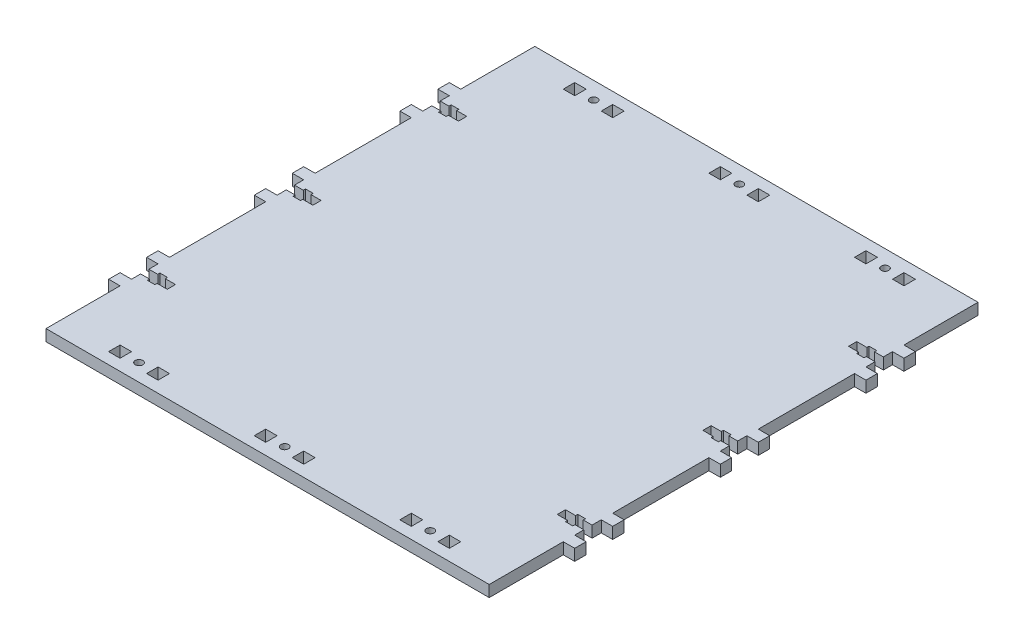
SolidWorks part; units mm, degrees
ref_plane "Front Plane" through (0, 0, 0) normal (0, 0, 1) x (1, 0, 0)
ref_plane "Top Plane" through (0, 0, 0) normal (0, 1, 0) x (1, 0, 0)
ref_plane "Right Plane" through (0, 0, 0) normal (1, 0, 0) x (0, 0, -1)
sketch "Sketch1" plane through (0, 0, 0) normal (0, 1, 0) x (1, 0, 0)
  line L0 (0, 0) -> (0, 159.925) construction
  line L1 (-175, -175) -> (175, -175) construction
  line L2 (-175, -175) -> (-175, 175) construction
  line L3 (-175, 175) -> (175, 175) construction
  line L4 (175, -175) -> (175, 175) construction
  line L5 (-175, -175) -> (175, 175) construction
  line L6 (-175, 175) -> (175, -175) construction
  line L7 (-175, -193) -> (175, -193)
  line L8 (-175, -193) -> (-175, 193)
  line L9 (-175, 193) -> (175, 193)
  line L10 (175, -193) -> (175, 193)
  line L11 (-175, -193) -> (175, 193) construction
  line L12 (-175, 193) -> (175, -193) construction
  line L13 (0, 0) -> (-128.731, 0) construction
  point P0 (0, 0)
  point P6 (0, 0)
  line B0 (0, 179.525) -> (-15, 179.525) construction
  line B1 (0, 184.9951) -> (0, 174.5131) construction
  line B2 (19.525, 184.05) -> (10.475, 184.05)
  line B3 (-19.525, 175) -> (-10.475, 175)
  line B4 (-19.525, 175) -> (-19.525, 184.05)
  line B5 (-19.525, 184.05) -> (-10.475, 184.05)
  line B6 (-10.475, 175) -> (-10.475, 184.05)
  line B7 (-19.525, 175) -> (-10.475, 184.05) construction
  line B8 (-19.525, 184.05) -> (-10.475, 175) construction
  line B9 (10.475, 175) -> (10.475, 184.05)
  line B10 (19.525, 175) -> (10.475, 175)
  line B11 (19.525, 175) -> (19.525, 184.05)
  circle B12 centre (0, 179.525) radius 3
  line B13 (-115, 179.525) -> (-130, 179.525) construction
  line B14 (-115, 184.9951) -> (-115, 174.5131) construction
  line B15 (-95.475, 184.05) -> (-104.525, 184.05)
  line B16 (-134.525, 175) -> (-125.475, 175)
  line B17 (-134.525, 175) -> (-134.525, 184.05)
  line B18 (-134.525, 184.05) -> (-125.475, 184.05)
  line B19 (-125.475, 175) -> (-125.475, 184.05)
  line B20 (-134.525, 175) -> (-125.475, 184.05) construction
  line B21 (-134.525, 184.05) -> (-125.475, 175) construction
  line B22 (-104.525, 175) -> (-104.525, 184.05)
  line B23 (-95.475, 175) -> (-104.525, 175)
  line B24 (-95.475, 175) -> (-95.475, 184.05)
  circle B25 centre (-115, 179.525) radius 3
  line B26 (-175, 19.5) -> (-184, 19.5)
  line B27 (-184, 19.5) -> (-184, 10.5)
  line B28 (-184, 10.5) -> (-175, 10.5)
  line B29 (-175, 10.5) -> (-175, 3.25)
  line B30 (-175, 3.25) -> (-168, 3.25)
  line B31 (-168, 3.25) -> (-168, 4.975)
  line B32 (-168, 4.975) -> (-162, 4.975)
  line B33 (-162, 4.975) -> (-162, 3.25)
  line B34 (-162, 3.25) -> (-154, 3.25)
  line B35 (-154, 3.25) -> (-154, -3.25)
  line B36 (-154, 0) -> (-175, 0) construction
  line B37 (-162, -3.25) -> (-154, -3.25)
  line B38 (-162, -4.975) -> (-162, -3.25)
  line B39 (-168, -4.975) -> (-162, -4.975)
  line B40 (-168, -3.25) -> (-168, -4.975)
  line B41 (-175, -3.25) -> (-168, -3.25)
  line B42 (-175, -10.5) -> (-175, -3.25)
  line B43 (-184, -10.5) -> (-175, -10.5)
  line B44 (-184, -19.5) -> (-184, -10.5)
  line B45 (-175, -19.5) -> (-184, -19.5)
  line B46 (-175, 134.5) -> (-184, 134.5)
  line B47 (-184, 134.5) -> (-184, 125.5)
  line B48 (-184, 125.5) -> (-175, 125.5)
  line B49 (-175, 125.5) -> (-175, 118.25)
  line B50 (-175, 118.25) -> (-168, 118.25)
  line B51 (-168, 118.25) -> (-168, 119.975)
  line B52 (-168, 119.975) -> (-162, 119.975)
  line B53 (-162, 119.975) -> (-162, 118.25)
  line B54 (-162, 118.25) -> (-154, 118.25)
  line B55 (-154, 118.25) -> (-154, 111.75)
  line B56 (-154, 115) -> (-175, 115) construction
  line B57 (-162, 111.75) -> (-154, 111.75)
  line B58 (-162, 110.025) -> (-162, 111.75)
  line B59 (-168, 110.025) -> (-162, 110.025)
  line B60 (-168, 111.75) -> (-168, 110.025)
  line B61 (-175, 111.75) -> (-168, 111.75)
  line B62 (-175, 104.5) -> (-175, 111.75)
  line B63 (-184, 104.5) -> (-175, 104.5)
  line B64 (-184, 95.5) -> (-184, 104.5)
  line B65 (-175, 95.5) -> (-184, 95.5)
  line B66 (115, 179.525) -> (130, 179.525) construction
  line B67 (115, 184.9951) -> (115, 174.5131) construction
  line B68 (95.475, 184.05) -> (104.525, 184.05)
  line B69 (134.525, 175) -> (125.475, 175)
  line B70 (134.525, 175) -> (134.525, 184.05)
  line B71 (134.525, 184.05) -> (125.475, 184.05)
  line B72 (125.475, 175) -> (125.475, 184.05)
  line B73 (134.525, 175) -> (125.475, 184.05) construction
  line B74 (134.525, 184.05) -> (125.475, 175) construction
  line B75 (104.525, 175) -> (104.525, 184.05)
  line B76 (95.475, 175) -> (104.525, 175)
  line B77 (95.475, 175) -> (95.475, 184.05)
  circle B78 centre (115, 179.525) radius 3
  line B79 (175, 19.5) -> (184, 19.5)
  line B80 (184, 19.5) -> (184, 10.5)
  line B81 (184, 10.5) -> (175, 10.5)
  line B82 (175, 10.5) -> (175, 3.25)
  line B83 (175, 3.25) -> (168, 3.25)
  line B84 (168, 3.25) -> (168, 4.975)
  line B85 (168, 4.975) -> (162, 4.975)
  line B86 (162, 4.975) -> (162, 3.25)
  line B87 (162, 3.25) -> (154, 3.25)
  line B88 (154, 3.25) -> (154, -3.25)
  line B89 (154, 0) -> (175, 0) construction
  line B90 (162, -3.25) -> (154, -3.25)
  line B91 (162, -4.975) -> (162, -3.25)
  line B92 (168, -4.975) -> (162, -4.975)
  line B93 (168, -3.25) -> (168, -4.975)
  line B94 (175, -3.25) -> (168, -3.25)
  line B95 (175, -10.5) -> (175, -3.25)
  line B96 (184, -10.5) -> (175, -10.5)
  line B97 (184, -19.5) -> (184, -10.5)
  line B98 (175, -19.5) -> (184, -19.5)
  line B99 (175, 134.5) -> (184, 134.5)
  line B100 (184, 134.5) -> (184, 125.5)
  line B101 (184, 125.5) -> (175, 125.5)
  line B102 (175, 125.5) -> (175, 118.25)
  line B103 (175, 118.25) -> (168, 118.25)
  line B104 (168, 118.25) -> (168, 119.975)
  line B105 (168, 119.975) -> (162, 119.975)
  line B106 (162, 119.975) -> (162, 118.25)
  line B107 (162, 118.25) -> (154, 118.25)
  line B108 (154, 118.25) -> (154, 111.75)
  line B109 (154, 115) -> (175, 115) construction
  line B110 (162, 111.75) -> (154, 111.75)
  line B111 (162, 110.025) -> (162, 111.75)
  line B112 (168, 110.025) -> (162, 110.025)
  line B113 (168, 111.75) -> (168, 110.025)
  line B114 (175, 111.75) -> (168, 111.75)
  line B115 (175, 104.5) -> (175, 111.75)
  line B116 (184, 104.5) -> (175, 104.5)
  line B117 (184, 95.5) -> (184, 104.5)
  line B118 (175, 95.5) -> (184, 95.5)
  line B119 (-115, -179.525) -> (-130, -179.525) construction
  line B120 (-115, -184.9951) -> (-115, -174.5131) construction
  line B121 (-95.475, -184.05) -> (-104.525, -184.05)
  line B122 (-134.525, -175) -> (-125.475, -175)
  line B123 (-134.525, -175) -> (-134.525, -184.05)
  line B124 (-134.525, -184.05) -> (-125.475, -184.05)
  line B125 (-125.475, -175) -> (-125.475, -184.05)
  line B126 (-134.525, -175) -> (-125.475, -184.05) construction
  line B127 (-134.525, -184.05) -> (-125.475, -175) construction
  line B128 (-104.525, -175) -> (-104.525, -184.05)
  line B129 (-95.475, -175) -> (-104.525, -175)
  line B130 (-95.475, -175) -> (-95.475, -184.05)
  circle B131 centre (-115, -179.525) radius 3
  line B132 (0, -179.525) -> (-15, -179.525) construction
  line B133 (0, -184.9951) -> (0, -174.5131) construction
  line B134 (19.525, -184.05) -> (10.475, -184.05)
  line B135 (-19.525, -175) -> (-10.475, -175)
  line B136 (-19.525, -175) -> (-19.525, -184.05)
  line B137 (-19.525, -184.05) -> (-10.475, -184.05)
  line B138 (-10.475, -175) -> (-10.475, -184.05)
  line B139 (-19.525, -175) -> (-10.475, -184.05) construction
  line B140 (-19.525, -184.05) -> (-10.475, -175) construction
  line B141 (10.475, -175) -> (10.475, -184.05)
  line B142 (19.525, -175) -> (10.475, -175)
  line B143 (19.525, -175) -> (19.525, -184.05)
  circle B144 centre (0, -179.525) radius 3
  line B145 (-175, -134.5) -> (-184, -134.5)
  line B146 (-184, -134.5) -> (-184, -125.5)
  line B147 (-184, -125.5) -> (-175, -125.5)
  line B148 (-175, -125.5) -> (-175, -118.25)
  line B149 (-175, -118.25) -> (-168, -118.25)
  line B150 (-168, -118.25) -> (-168, -119.975)
  line B151 (-168, -119.975) -> (-162, -119.975)
  line B152 (-162, -119.975) -> (-162, -118.25)
  line B153 (-162, -118.25) -> (-154, -118.25)
  line B154 (-154, -118.25) -> (-154, -111.75)
  line B155 (-154, -115) -> (-175, -115) construction
  line B156 (-162, -111.75) -> (-154, -111.75)
  line B157 (-162, -110.025) -> (-162, -111.75)
  line B158 (-168, -110.025) -> (-162, -110.025)
  line B159 (-168, -111.75) -> (-168, -110.025)
  line B160 (-175, -111.75) -> (-168, -111.75)
  line B161 (-175, -104.5) -> (-175, -111.75)
  line B162 (-184, -104.5) -> (-175, -104.5)
  line B163 (-184, -95.5) -> (-184, -104.5)
  line B164 (-175, -95.5) -> (-184, -95.5)
  line B165 (175, -134.5) -> (184, -134.5)
  line B166 (184, -134.5) -> (184, -125.5)
  line B167 (184, -125.5) -> (175, -125.5)
  line B168 (175, -125.5) -> (175, -118.25)
  line B169 (175, -118.25) -> (168, -118.25)
  line B170 (168, -118.25) -> (168, -119.975)
  line B171 (168, -119.975) -> (162, -119.975)
  line B172 (162, -119.975) -> (162, -118.25)
  line B173 (162, -118.25) -> (154, -118.25)
  line B174 (154, -118.25) -> (154, -111.75)
  line B175 (154, -115) -> (175, -115) construction
  line B176 (162, -111.75) -> (154, -111.75)
  line B177 (162, -110.025) -> (162, -111.75)
  line B178 (168, -110.025) -> (162, -110.025)
  line B179 (168, -111.75) -> (168, -110.025)
  line B180 (175, -111.75) -> (168, -111.75)
  line B181 (175, -104.5) -> (175, -111.75)
  line B182 (184, -104.5) -> (175, -104.5)
  line B183 (184, -95.5) -> (184, -104.5)
  line B184 (175, -95.5) -> (184, -95.5)
  line B185 (115, -179.525) -> (130, -179.525) construction
  line B186 (115, -184.9951) -> (115, -174.5131) construction
  line B187 (95.475, -184.05) -> (104.525, -184.05)
  line B188 (134.525, -175) -> (125.475, -175)
  line B189 (134.525, -175) -> (134.525, -184.05)
  line B190 (134.525, -184.05) -> (125.475, -184.05)
  line B191 (125.475, -175) -> (125.475, -184.05)
  line B192 (134.525, -175) -> (125.475, -184.05) construction
  line B193 (134.525, -184.05) -> (125.475, -175) construction
  line B194 (104.525, -175) -> (104.525, -184.05)
  line B195 (95.475, -175) -> (104.525, -175)
  line B196 (95.475, -175) -> (95.475, -184.05)
  circle B197 centre (115, -179.525) radius 3
  dimension "D1" = 350
  dimension "D2" = 350
  dimension "D3" = 18
  dimension "D4" = 60
  dimension "D5" = 60
sketch_block_instance "Insert_9mm_M6_bois-1"
sketch_block "Insert_9mm_M6_bois" parameters "D4"=6, "D1"=9.05, "D2"=9.05, "D3"=15
sketch_block_instance "Insert_9mm_M6_bois-2"
sketch_block_instance "Plot_9mm_M6_bois-1"
sketch_block "Plot_9mm_M6_bois" parameters "D1"=9, "D2"=9, "D3"=16, "D4"=30, "D5"=9.95, "D6"=6.5, "D7"=6, "D8"=8
sketch_block_instance "Plot_9mm_M6_bois-4"
sketch_block_instance "Insert_9mm_M6_bois-4"
sketch_block_instance "Plot_9mm_M6_bois-5"
sketch_block_instance "Plot_9mm_M6_bois-6"
sketch_block_instance "Insert_9mm_M6_bois-5"
sketch_block_instance "Insert_9mm_M6_bois-6"
sketch_block_instance "Plot_9mm_M6_bois-7"
sketch_block_instance "Plot_9mm_M6_bois-8"
sketch_block_instance "Insert_9mm_M6_bois-7"
extrude "Boss-Extrude1" add sketch "Sketch1" along normal blind 9 contours L8 B164 B163 B162 | B27 B28 L8 B26 | B45 L8 B43 B44 | B147 B146 B145 L8 | B65 L8 B63 B64 | B47 B48 L8 B46 | B180 L10 B94 B93 B92 B91 B90 B88 B87 B86 B85 B84 B83 B114 B113 B112 B111 B110 B108 B107 B106 B105 B104 B103 L9 L8 B50 B51 B52 B53 B54 B55 B57 B58 B59 B60 B61 | B166 B167 L10 B165 | B184 L10 B182 B183 | L10 B98 B97 B96 | B81 B80 B79 L10 | B101 B100 B99 L10 | L10 B118 B117 B116
